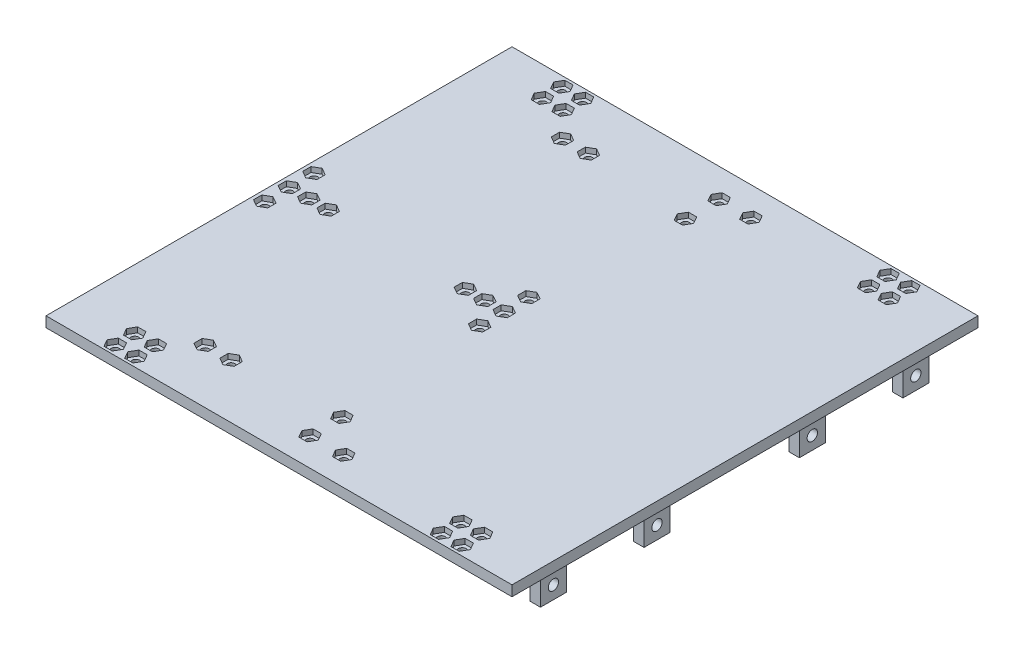
SolidWorks part; units mm, degrees
ref_plane "Alzado" through (0, 0, 0) normal (0, 0, 1) x (1, 0, 0)
ref_plane "Planta" through (0, 0, 0) normal (0, 1, 0) x (1, 0, 0)
ref_plane "Vista lateral" through (0, 0, 0) normal (1, 0, 0) x (0, 0, -1)
sketch "Croquis2" plane through (0, 0, 0) normal (0, 1, 0) x (1, 0, 0)
  line L1 (90, -90) -> (-90, -90)
  line L2 (90, -90) -> (90, 90)
  line L3 (90, 90) -> (-90, 90)
  line L4 (-90, -90) -> (-90, 90)
  line L5 (90, -90) -> (-90, 90) construction
  line L6 (90, 90) -> (-90, -90) construction
  point P0 (0, 0)
extrude "Saliente-Extruir2" add sketch "Croquis2" along normal blind 4
sketch "Croquis3" plane through (0, 0, 0) normal (0, -1, 0) x (1, 0, 0)
  line L0 (-90, 0) -> (90, 0) construction
  line L1 (-86, 75) -> (-82, 75)
  line L2 (-86, 75) -> (-86, 65)
  line L3 (-86, 65) -> (-82, 65)
  line L4 (-82, 75) -> (-82, 65)
  line L5 (-86, 75) -> (-82, 65) construction
  line L6 (-86, 65) -> (-82, 75) construction
  line L7 (-90, -90) -> (-90, 90) construction
  line L8 (90, 90) -> (90, -90) construction
  line L9 (-90, 90) -> (90, 90) construction
  line L10 (-82, 35) -> (-82, 25)
  line L11 (-86, 35) -> (-86, 25)
  line L12 (-86, 35) -> (-82, 35)
  line L13 (-86, 25) -> (-82, 25)
  line L14 (0, 90) -> (0, -90) construction
  line L16 (90, -90) -> (-90, -90) construction
  line L17 (86, 65) -> (82, 75) construction
  line L26 (86, 75) -> (82, 65) construction
  line L27 (86, 25) -> (82, 25)
  line L28 (86, 35) -> (82, 35)
  line L29 (86, 35) -> (86, 25)
  line L30 (82, 35) -> (82, 25)
  line L31 (82, 75) -> (82, 65)
  line L32 (86, 65) -> (82, 65)
  line L33 (86, 75) -> (86, 65)
  line L34 (86, 75) -> (82, 75)
  line L35 (86, -75) -> (82, -65) construction
  line L36 (86, -65) -> (82, -75) construction
  line L37 (86, -75) -> (82, -75)
  line L38 (86, -75) -> (86, -65)
  line L39 (86, -65) -> (82, -65)
  line L40 (82, -75) -> (82, -65)
  line L41 (82, -35) -> (82, -25)
  line L42 (86, -35) -> (86, -25)
  line L43 (86, -35) -> (82, -35)
  line L44 (86, -25) -> (82, -25)
  line L45 (-86, -65) -> (-82, -75) construction
  line L46 (-86, -75) -> (-82, -65) construction
  line L47 (-86, -25) -> (-82, -25)
  line L48 (-86, -35) -> (-82, -35)
  line L49 (-86, -35) -> (-86, -25)
  line L50 (-82, -35) -> (-82, -25)
  line L51 (-82, -75) -> (-82, -65)
  line L52 (-86, -65) -> (-82, -65)
  line L53 (-86, -75) -> (-86, -65)
  line L54 (-86, -75) -> (-82, -75)
  point P0 (-84, 70)
  point P29 (84, 70)
  point P38 (84, -70)
  point P47 (-84, -70)
  dimension "D1" = 4
  dimension "D2" = 15
  dimension "D3" = 10
  dimension "D4" = 4
  dimension "D6" = 30
  dimension "D5" = 2
extrude "Saliente-Extruir3" add sketch "Croquis3" along normal blind 13
sketch "Croquis4" plane through (86, 0, 0) normal (1, 0, 0) x (0, 0, -1)
  line L0 (-65, -13) -> (-75, -13) construction
  line L1 (-65, -13) -> (-65, 0) construction
  line L2 (-35, -13) -> (-35, 0) construction
  line L3 (25, -13) -> (25, 0) construction
  line L4 (65, -13) -> (65, 0) construction
  circle A0 centre (-70, -8) radius 2
  circle A1 centre (-30, -8) radius 2
  circle A2 centre (30, -8) radius 2
  circle A3 centre (70, -8) radius 2
  dimension "D1" = 4
  dimension "D4" = 5
  dimension "D2" = 5
  dimension "D3" = 5
  dimension "D5" = 5
  dimension "D6" = 5
extrude "Cortar-Extruir1" cut sketch "Croquis4" along direction (1, 0, 0) on the side against the normal up to surface (172 mm away)
sketch "Croquis5" plane through (86, 0, 0) normal (1, 0, 0) x (0, 0, -1)
  line L1 (35, -3) -> (40.7629, -3)
  line L4 (-35, -13) -> (-35, 0) construction
  line L5 (-65, 0) -> (-35, 0) construction
  line L6 (40.7629, -3) -> (35, 0)
  line L10 (65, -13) -> (65, 0) construction
  line L11 (35, 0) -> (65, 0) construction
  line L13 (59.2371, -3) -> (65, 0)
  line L19 (-65, 0) -> (-65, -3)
  line L24 (-65, -3) -> (-35, -3) construction
  line L25 (-35, 0) -> (-35, -3)
  line L30 (35, 0) -> (35, -3)
  line L31 (35, -3) -> (65, -3) construction
  line L32 (-65, 0) -> (-35, -3) construction
  line L33 (-65, -3) -> (-35, 0) construction
  line L34 (65, 0) -> (65, -3)
  line L35 (35, 0) -> (65, -3) construction
  line L36 (35, -3) -> (65, 0) construction
  line L41 (-65, -3) -> (-59.2371, -3)
  line L42 (-59.2371, -3) -> (-65, 0)
  line L43 (-35, 0) -> (-40.7629, -3)
  line L44 (-40.7629, -3) -> (-35, -3)
  line L45 (59.2371, -3) -> (65, -3)
  point P5 (-50, -1.5)
  point P14 (50, -1.5)
  dimension "D1" = 3
  dimension "D2" = 3
  dimension "D3" = 27.5
  dimension "D4" = 27.5
  dimension "D5" = 27.5
  dimension "D6" = 27.5
extrude "Saliente-Extruir7" add sketch "Croquis5" against normal blind 75 separate body
sketch "Croquis7" plane through (-86, 0, 0) normal (-1, 0, 0) x (0, 0, 1)
  line L0 (65, 0) -> (59.2371, -3) construction
  line L1 (59.2371, -3) -> (65, -3) construction
  line L2 (65, -3) -> (65, 0) construction
  line L3 (35, -3) -> (40.7629, -3) construction
  line L4 (40.7629, -3) -> (35, 0) construction
  line L5 (35, 0) -> (35, -3) construction
  line L6 (-35, 0) -> (-40.7629, -3) construction
  line L7 (-40.7629, -3) -> (-35, -3) construction
  line L8 (-35, -3) -> (-35, 0) construction
  line L9 (-65, -3) -> (-59.2371, -3) construction
  line L10 (-59.2371, -3) -> (-65, 0) construction
  line L11 (-65, 0) -> (-65, -3) construction
  line L12 (65, 0) -> (59.2371, -3)
  line L13 (59.2371, -3) -> (65, -3)
  line L14 (65, -3) -> (65, 0)
  line L15 (35, -3) -> (40.7629, -3)
  line L16 (40.7629, -3) -> (35, 0)
  line L17 (35, 0) -> (35, -3)
  line L18 (-35, 0) -> (-40.7629, -3)
  line L19 (-40.7629, -3) -> (-35, -3)
  line L20 (-35, -3) -> (-35, 0)
  line L21 (-65, -3) -> (-59.2371, -3)
  line L22 (-59.2371, -3) -> (-65, 0)
  line L23 (-65, 0) -> (-65, -3)
extrude "Saliente-Extruir8" add sketch "Croquis7" against normal blind 75 separate body
sketch "Croquis8" plane through (0, 4, 0) normal (0, 1, 0) x (1, 0, 0)
  circle A0 centre (67, -86.25) radius 1.5
  circle A1 centre (59, -86.25) radius 1.5
  circle A2 centre (59, -78.75) radius 1.5
  circle A3 centre (67, -78.75) radius 1.5
  circle A4 centre (14, -79) radius 1.5
  circle A5 centre (1, -79) radius 1.5
  circle A6 centre (1, -66.715) radius 1.5
  circle A7 centre (67, 78.75) radius 1.5
  circle A8 centre (67, 86.25) radius 1.5
  circle A9 centre (59, 86.25) radius 1.5
  circle A10 centre (59, 78.75) radius 1.5
  circle A11 centre (13.285, 79) radius 1.5
  circle A12 centre (1, 79) radius 1.5
  circle A13 centre (1, 66) radius 1.5
  circle A14 centre (-59, 78.75) radius 1.5
  circle A15 centre (-67, 78.75) radius 1.5
  circle A16 centre (-67, 86.25) radius 1.5
  circle A18 centre (-59, 86.25) radius 1.5
  circle A19 centre (-59, -78.75) radius 1.5
  circle A20 centre (-59, -86.25) radius 1.5
  circle A21 centre (-67, -78.75) radius 1.5
  circle A22 centre (-67, -86.25) radius 1.5
extrude "Cortar-Extruir2" cut sketch "Croquis8" against normal up to next (4 mm away)
sketch "Croquis9" plane through (0, 4, 0) normal (0, 1, 0) x (1, 0, 0)
  line L1 (65.4123, -89) -> (68.5877, -89)
  line L2 (68.5877, -89) -> (70.1754, -86.25)
  line L3 (70.1754, -86.25) -> (68.5877, -83.5)
  line L4 (68.5877, -83.5) -> (65.4123, -83.5)
  line L5 (65.4123, -83.5) -> (63.8246, -86.25)
  line L6 (63.8246, -86.25) -> (65.4123, -89)
  line L7 (57.4123, -89) -> (60.5877, -89)
  line L8 (60.5877, -89) -> (62.1754, -86.25)
  line L9 (62.1754, -86.25) -> (60.5877, -83.5)
  line L10 (60.5877, -83.5) -> (57.4123, -83.5)
  line L11 (57.4123, -83.5) -> (55.8246, -86.25)
  line L12 (55.8246, -86.25) -> (57.4123, -89)
  line L13 (57.4123, -81.5) -> (60.5877, -81.5)
  line L14 (60.5877, -81.5) -> (62.1754, -78.75)
  line L15 (62.1754, -78.75) -> (60.5877, -76)
  line L16 (60.5877, -76) -> (57.4123, -76)
  line L17 (57.4123, -76) -> (55.8246, -78.75)
  line L18 (55.8246, -78.75) -> (57.4123, -81.5)
  line L19 (65.4123, -81.5) -> (68.5877, -81.5)
  line L20 (68.5877, -81.5) -> (70.1754, -78.75)
  line L21 (70.1754, -78.75) -> (68.5877, -76)
  line L22 (68.5877, -76) -> (65.4123, -76)
  line L23 (65.4123, -76) -> (63.8246, -78.75)
  line L24 (63.8246, -78.75) -> (65.4123, -81.5)
  line L25 (15.5877, -81.75) -> (17.1754, -79)
  line L26 (17.1754, -79) -> (15.5877, -76.25)
  line L27 (15.5877, -76.25) -> (12.4123, -76.25)
  line L28 (12.4123, -76.25) -> (10.8246, -79)
  line L29 (10.8246, -79) -> (12.4123, -81.75)
  line L30 (12.4123, -81.75) -> (15.5877, -81.75)
  line L31 (2.5877, -81.75) -> (4.1754, -79)
  line L32 (4.1754, -79) -> (2.5877, -76.25)
  line L33 (2.5877, -76.25) -> (-0.5877, -76.25)
  line L34 (-0.5877, -76.25) -> (-2.1754, -79)
  line L35 (-2.1754, -79) -> (-0.5877, -81.75)
  line L36 (-0.5877, -81.75) -> (2.5877, -81.75)
  line L37 (2.5877, -69.465) -> (4.1754, -66.715)
  line L38 (4.1754, -66.715) -> (2.5877, -63.965)
  line L39 (2.5877, -63.965) -> (-0.5877, -63.965)
  line L40 (-0.5877, -63.965) -> (-2.1754, -66.715)
  line L41 (-2.1754, -66.715) -> (-0.5877, -69.465)
  line L42 (-0.5877, -69.465) -> (2.5877, -69.465)
  line L67 (68.5877, 76) -> (70.1754, 78.75)
  line L68 (70.1754, 78.75) -> (68.5877, 81.5)
  line L69 (68.5877, 81.5) -> (65.4123, 81.5)
  line L70 (65.4123, 81.5) -> (63.8246, 78.75)
  line L71 (63.8246, 78.75) -> (65.4123, 76)
  line L72 (65.4123, 76) -> (68.5877, 76)
  line L73 (60.5877, 76) -> (62.1754, 78.75)
  line L74 (62.1754, 78.75) -> (60.5877, 81.5)
  line L75 (60.5877, 81.5) -> (57.4123, 81.5)
  line L76 (57.4123, 81.5) -> (55.8246, 78.75)
  line L77 (55.8246, 78.75) -> (57.4123, 76)
  line L78 (57.4123, 76) -> (60.5877, 76)
  line L79 (68.5877, 83.5) -> (70.1754, 86.25)
  line L80 (70.1754, 86.25) -> (68.5877, 89)
  line L81 (68.5877, 89) -> (65.4123, 89)
  line L82 (65.4123, 89) -> (63.8246, 86.25)
  line L83 (63.8246, 86.25) -> (65.4123, 83.5)
  line L84 (65.4123, 83.5) -> (68.5877, 83.5)
  line L85 (60.5877, 83.5) -> (62.1754, 86.25)
  line L86 (62.1754, 86.25) -> (60.5877, 89)
  line L87 (60.5877, 89) -> (57.4123, 89)
  line L88 (57.4123, 89) -> (55.8246, 86.25)
  line L89 (55.8246, 86.25) -> (57.4123, 83.5)
  line L90 (57.4123, 83.5) -> (60.5877, 83.5)
  line L91 (14.8727, 76.25) -> (16.4604, 79)
  line L92 (16.4604, 79) -> (14.8727, 81.75)
  line L93 (14.8727, 81.75) -> (11.6972, 81.75)
  line L94 (11.6972, 81.75) -> (10.1095, 79)
  line L95 (10.1095, 79) -> (11.6972, 76.25)
  line L96 (11.6972, 76.25) -> (14.8727, 76.25)
  line L97 (2.5877, 76.25) -> (4.1754, 79)
  line L98 (4.1754, 79) -> (2.5877, 81.75)
  line L99 (2.5877, 81.75) -> (-0.5877, 81.75)
  line L100 (-0.5877, 81.75) -> (-2.1754, 79)
  line L101 (-2.1754, 79) -> (-0.5877, 76.25)
  line L102 (-0.5877, 76.25) -> (2.5877, 76.25)
  line L103 (2.5877, 63.25) -> (4.1754, 66)
  line L104 (4.1754, 66) -> (2.5877, 68.75)
  line L105 (2.5877, 68.75) -> (-0.5877, 68.75)
  line L106 (-0.5877, 68.75) -> (-2.1754, 66)
  line L107 (-2.1754, 66) -> (-0.5877, 63.25)
  line L108 (-0.5877, 63.25) -> (2.5877, 63.25)
  line L109 (-65.4123, 83.5) -> (-63.8246, 86.25)
  line L110 (-63.8246, 86.25) -> (-65.4123, 89)
  line L111 (-65.4123, 89) -> (-68.5877, 89)
  line L112 (-68.5877, 89) -> (-70.1754, 86.25)
  line L113 (-70.1754, 86.25) -> (-68.5877, 83.5)
  line L114 (-68.5877, 83.5) -> (-65.4123, 83.5)
  line L115 (-57.4123, 83.5) -> (-55.8246, 86.25)
  line L116 (-55.8246, 86.25) -> (-57.4123, 89)
  line L117 (-57.4123, 89) -> (-60.5877, 89)
  line L118 (-60.5877, 89) -> (-62.1754, 86.25)
  line L119 (-62.1754, 86.25) -> (-60.5877, 83.5)
  line L120 (-60.5877, 83.5) -> (-57.4123, 83.5)
  line L121 (-57.4123, 76) -> (-55.8246, 78.75)
  line L122 (-55.8246, 78.75) -> (-57.4123, 81.5)
  line L123 (-57.4123, 81.5) -> (-60.5877, 81.5)
  line L124 (-60.5877, 81.5) -> (-62.1754, 78.75)
  line L125 (-62.1754, 78.75) -> (-60.5877, 76)
  line L126 (-60.5877, 76) -> (-57.4123, 76)
  line L127 (-65.4123, 76) -> (-63.8246, 78.75)
  line L128 (-63.8246, 78.75) -> (-65.4123, 81.5)
  line L129 (-65.4123, 81.5) -> (-68.5877, 81.5)
  line L130 (-68.5877, 81.5) -> (-70.1754, 78.75)
  line L131 (-70.1754, 78.75) -> (-68.5877, 76)
  line L132 (-68.5877, 76) -> (-65.4123, 76)
  line L133 (-57.4123, -89) -> (-55.8246, -86.25)
  line L134 (-55.8246, -86.25) -> (-57.4123, -83.5)
  line L135 (-57.4123, -83.5) -> (-60.5877, -83.5)
  line L136 (-60.5877, -83.5) -> (-62.1754, -86.25)
  line L137 (-62.1754, -86.25) -> (-60.5877, -89)
  line L138 (-60.5877, -89) -> (-57.4123, -89)
  line L139 (-65.4123, -89) -> (-63.8246, -86.25)
  line L140 (-63.8246, -86.25) -> (-65.4123, -83.5)
  line L141 (-65.4123, -83.5) -> (-68.5877, -83.5)
  line L142 (-68.5877, -83.5) -> (-70.1754, -86.25)
  line L143 (-70.1754, -86.25) -> (-68.5877, -89)
  line L144 (-68.5877, -89) -> (-65.4123, -89)
  line L145 (-57.4123, -81.5) -> (-55.8246, -78.75)
  line L146 (-55.8246, -78.75) -> (-57.4123, -76)
  line L147 (-57.4123, -76) -> (-60.5877, -76)
  line L148 (-60.5877, -76) -> (-62.1754, -78.75)
  line L149 (-62.1754, -78.75) -> (-60.5877, -81.5)
  line L150 (-60.5877, -81.5) -> (-57.4123, -81.5)
  line L151 (-65.4123, -81.5) -> (-63.8246, -78.75)
  line L152 (-63.8246, -78.75) -> (-65.4123, -76)
  line L153 (-65.4123, -76) -> (-68.5877, -76)
  line L154 (-68.5877, -76) -> (-70.1754, -78.75)
  line L155 (-70.1754, -78.75) -> (-68.5877, -81.5)
  line L156 (-68.5877, -81.5) -> (-65.4123, -81.5)
  circle A0 centre (67, -86.25) radius 2.75 construction
  circle A1 centre (59, -86.25) radius 2.75 construction
  circle A2 centre (59, -78.75) radius 2.75 construction
  circle A3 centre (67, -78.75) radius 2.75 construction
  circle A4 centre (14, -79) radius 2.75 construction
  circle A5 centre (1, -79) radius 2.75 construction
  circle A6 centre (1, -66.715) radius 2.75 construction
  circle A7 centre (-59, -86.25) radius 2.75 construction
  circle A8 centre (-67, -86.25) radius 2.75 construction
  circle A9 centre (-59, -78.75) radius 2.75 construction
  circle A10 centre (-67, -78.75) radius 2.75 construction
  circle A11 centre (67, 78.75) radius 2.75 construction
  circle A12 centre (59, 78.75) radius 2.75 construction
  circle A13 centre (67, 86.25) radius 2.75 construction
  circle A14 centre (59, 86.25) radius 2.75 construction
  circle A15 centre (13.285, 79) radius 2.75 construction
  circle A16 centre (1, 79) radius 2.75 construction
  circle A17 centre (1, 66) radius 2.75 construction
  circle A18 centre (-67, 86.25) radius 2.75 construction
  circle A19 centre (-59, 86.25) radius 2.75 construction
  circle A20 centre (-59, 78.75) radius 2.75 construction
  circle A21 centre (-67, 78.75) radius 2.75 construction
  dimension "D1" = 5.5
  dimension "D2" = 5.5
  dimension "D3" = 5.5
  dimension "D4" = 5.5
  dimension "D5" = 5.5
  dimension "D6" = 5.5
  dimension "D7" = 5.5
  dimension "D8" = 5.5
  dimension "D9" = 5.5
  dimension "D10" = 5.5
  dimension "D11" = 5.5
  dimension "D12" = 5.5
  dimension "D13" = 5.5
  dimension "D14" = 5.5
  dimension "D15" = 5.5
  dimension "D16" = 5.5
  dimension "D17" = 5.5
  dimension "D18" = 5.5
  dimension "D19" = 5.5
  dimension "D20" = 5.5
  dimension "D21" = 5.5
  dimension "D22" = 5.5
extrude "Cortar-Extruir3" cut sketch "Croquis9" against normal blind 2
sketch "Croquis10" plane through (0, 4, 0) normal (0, 1, 0) x (1, 0, 0)
  circle A0 centre (-49.5, -69) radius 1.5
  circle A2 centre (-78.5, 0) radius 1.5 construction
  circle A3 centre (-86, 9.5) radius 1.5 construction
  circle A4 centre (-86, -9.5) radius 1.5 construction
  circle A5 centre (-86, 0) radius 1.5 construction
  circle A7 centre (-78.5, 0) radius 1.5
  circle A8 centre (-86, 9.5) radius 1.5
  circle A9 centre (-86, -9.5) radius 1.5
  circle A10 centre (-86, 0) radius 1.5
  circle A11 centre (-39.5, -69) radius 1.5
  circle A12 centre (-10.5, 0) radius 1.5 construction
  circle A13 centre (-3, 9.5) radius 1.5 construction
  circle A14 centre (-3, 0) radius 1.5 construction
  circle A15 centre (-3, -9.5) radius 1.5 construction
  circle A16 centre (-39.5, 69) radius 1.5 construction
  circle A17 centre (-49.5, 69) radius 1.5 construction
  circle A18 centre (-71, 0) radius 1.5 construction
  circle A19 centre (-10.5, 0) radius 1.5
  circle A20 centre (-3, 9.5) radius 1.5
  circle A21 centre (-3, 0) radius 1.5
  circle A22 centre (-3, -9.5) radius 1.5
  circle A23 centre (-39.5, 69) radius 1.5
  circle A24 centre (-49.5, 69) radius 1.5
  circle A25 centre (-71, 0) radius 1.5
  circle A26 centre (-18, 0) radius 1.5 construction
  circle A27 centre (-18, 0) radius 1.5
  dimension "D1" = 3
  dimension "D2" = 20.6754
  dimension "D3" = 30.6754
  dimension "D4" = 12.75
extrude "Cortar-Extruir4" cut sketch "Croquis10" against normal up to next (4 mm away)
sketch "Croquis11" plane through (0, 4, 0) normal (0, 1, 0) x (1, 0, 0)
  line L1 (-88.75, -11.0877) -> (-86, -12.6754)
  line L2 (-86, -12.6754) -> (-83.25, -11.0877)
  line L3 (-83.25, -11.0877) -> (-83.25, -7.9123)
  line L4 (-83.25, -7.9123) -> (-86, -6.3246)
  line L5 (-86, -6.3246) -> (-88.75, -7.9123)
  line L6 (-88.75, -7.9123) -> (-88.75, -11.0877)
  line L7 (-88.75, -1.5877) -> (-86, -3.1754)
  line L8 (-86, -3.1754) -> (-83.25, -1.5877)
  line L9 (-83.25, -1.5877) -> (-83.25, 1.5877)
  line L10 (-83.25, 1.5877) -> (-86, 3.1754)
  line L11 (-86, 3.1754) -> (-88.75, 1.5877)
  line L12 (-88.75, 1.5877) -> (-88.75, -1.5877)
  line L13 (-88.75, 7.9123) -> (-86, 6.3246)
  line L14 (-86, 6.3246) -> (-83.25, 7.9123)
  line L15 (-83.25, 7.9123) -> (-83.25, 11.0877)
  line L16 (-83.25, 11.0877) -> (-86, 12.6754)
  line L17 (-86, 12.6754) -> (-88.75, 11.0877)
  line L18 (-88.75, 11.0877) -> (-88.75, 7.9123)
  line L19 (-81.25, -1.5877) -> (-78.5, -3.1754)
  line L20 (-78.5, -3.1754) -> (-75.75, -1.5877)
  line L21 (-75.75, -1.5877) -> (-75.75, 1.5877)
  line L22 (-75.75, 1.5877) -> (-78.5, 3.1754)
  line L23 (-78.5, 3.1754) -> (-81.25, 1.5877)
  line L24 (-81.25, 1.5877) -> (-81.25, -1.5877)
  line L25 (-73.75, -1.5877) -> (-71, -3.1754)
  line L26 (-71, -3.1754) -> (-68.25, -1.5877)
  line L27 (-68.25, -1.5877) -> (-68.25, 1.5877)
  line L28 (-68.25, 1.5877) -> (-71, 3.1754)
  line L29 (-71, 3.1754) -> (-73.75, 1.5877)
  line L30 (-73.75, 1.5877) -> (-73.75, -1.5877)
  line L31 (-52.25, 67.4123) -> (-49.5, 65.8246)
  line L32 (-49.5, 65.8246) -> (-46.75, 67.4123)
  line L33 (-46.75, 67.4123) -> (-46.75, 70.5877)
  line L34 (-46.75, 70.5877) -> (-49.5, 72.1754)
  line L35 (-49.5, 72.1754) -> (-52.25, 70.5877)
  line L36 (-52.25, 70.5877) -> (-52.25, 67.4123)
  line L37 (-42.25, 67.4123) -> (-39.5, 65.8246)
  line L38 (-39.5, 65.8246) -> (-36.75, 67.4123)
  line L39 (-36.75, 67.4123) -> (-36.75, 70.5877)
  line L40 (-36.75, 70.5877) -> (-39.5, 72.1754)
  line L41 (-39.5, 72.1754) -> (-42.25, 70.5877)
  line L42 (-42.25, 70.5877) -> (-42.25, 67.4123)
  line L43 (-5.75, -11.0877) -> (-3, -12.6754)
  line L44 (-3, -12.6754) -> (-0.25, -11.0877)
  line L45 (-0.25, -11.0877) -> (-0.25, -7.9123)
  line L46 (-0.25, -7.9123) -> (-3, -6.3246)
  line L47 (-3, -6.3246) -> (-5.75, -7.9123)
  line L48 (-5.75, -7.9123) -> (-5.75, -11.0877)
  line L49 (-5.75, -1.5877) -> (-3, -3.1754)
  line L50 (-3, -3.1754) -> (-0.25, -1.5877)
  line L51 (-0.25, -1.5877) -> (-0.25, 1.5877)
  line L52 (-0.25, 1.5877) -> (-3, 3.1754)
  line L53 (-3, 3.1754) -> (-5.75, 1.5877)
  line L54 (-5.75, 1.5877) -> (-5.75, -1.5877)
  line L55 (-5.75, 7.9123) -> (-3, 6.3246)
  line L56 (-3, 6.3246) -> (-0.25, 7.9123)
  line L57 (-0.25, 7.9123) -> (-0.25, 11.0877)
  line L58 (-0.25, 11.0877) -> (-3, 12.6754)
  line L59 (-3, 12.6754) -> (-5.75, 11.0877)
  line L60 (-5.75, 11.0877) -> (-5.75, 7.9123)
  line L61 (-13.25, -1.5877) -> (-10.5, -3.1754)
  line L62 (-10.5, -3.1754) -> (-7.75, -1.5877)
  line L63 (-7.75, -1.5877) -> (-7.75, 1.5877)
  line L64 (-7.75, 1.5877) -> (-10.5, 3.1754)
  line L65 (-10.5, 3.1754) -> (-13.25, 1.5877)
  line L66 (-13.25, 1.5877) -> (-13.25, -1.5877)
  line L67 (-20.75, -1.5877) -> (-18, -3.1754)
  line L68 (-18, -3.1754) -> (-15.25, -1.5877)
  line L69 (-15.25, -1.5877) -> (-15.25, 1.5877)
  line L70 (-15.25, 1.5877) -> (-18, 3.1754)
  line L71 (-18, 3.1754) -> (-20.75, 1.5877)
  line L72 (-20.75, 1.5877) -> (-20.75, -1.5877)
  line L73 (-52.25, -70.5877) -> (-49.5, -72.1754)
  line L74 (-49.5, -72.1754) -> (-46.75, -70.5877)
  line L75 (-46.75, -70.5877) -> (-46.75, -67.4123)
  line L76 (-46.75, -67.4123) -> (-49.5, -65.8246)
  line L77 (-49.5, -65.8246) -> (-52.25, -67.4123)
  line L78 (-52.25, -67.4123) -> (-52.25, -70.5877)
  line L79 (-42.25, -70.5877) -> (-39.5, -72.1754)
  line L80 (-39.5, -72.1754) -> (-36.75, -70.5877)
  line L81 (-36.75, -70.5877) -> (-36.75, -67.4123)
  line L82 (-36.75, -67.4123) -> (-39.5, -65.8246)
  line L83 (-39.5, -65.8246) -> (-42.25, -67.4123)
  line L84 (-42.25, -67.4123) -> (-42.25, -70.5877)
  circle A0 centre (-86, -9.5) radius 2.75 construction
  circle A1 centre (-86, 0) radius 2.75 construction
  circle A2 centre (-86, 9.5) radius 2.75 construction
  circle A3 centre (-78.5, 0) radius 2.75 construction
  circle A4 centre (-71, 0) radius 2.75 construction
  circle A5 centre (-49.5, 69) radius 2.75 construction
  circle A6 centre (-39.5, 69) radius 2.75 construction
  circle A7 centre (-3, -9.5) radius 2.75 construction
  circle A8 centre (-3, 0) radius 2.75 construction
  circle A9 centre (-3, 9.5) radius 2.75 construction
  circle A10 centre (-10.5, 0) radius 2.75 construction
  circle A11 centre (-18, 0) radius 2.75 construction
  circle A12 centre (-49.5, -69) radius 2.75 construction
  circle A13 centre (-39.5, -69) radius 2.75 construction
  dimension "D1" = 5.5
  dimension "D2" = 5.5
  dimension "D3" = 5.5
  dimension "D4" = 5.5
extrude "Cortar-Extruir5" cut sketch "Croquis11" against normal blind 2
sketch "Croquis12" plane through (11, 0, 0) normal (-1, 0, 0) x (0, 0, 1)
  line L0 (-65, -3) -> (-59.2371, -3) construction
  line L1 (-59.2371, -3) -> (-65, 0) construction
  line L2 (-65, 0) -> (-65, -3) construction
  line L3 (35, -3) -> (40.7629, -3)
  line L4 (40.7629, -3) -> (35, 0)
  line L5 (35, 0) -> (35, -3)
  line L7 (40.7629, -3) -> (35, 0) construction
  line L8 (35, 0) -> (35, -3)
  line L9 (-35, 0) -> (-40.7629, -3) construction
  line L10 (-40.7629, -3) -> (-35, -3) construction
  line L11 (-35, -3) -> (-35, 0) construction
  line L12 (65, 0) -> (59.2371, -3) construction
  line L13 (59.2371, -3) -> (65, -3) construction
  line L14 (65, -3) -> (65, 0) construction
  line L15 (-65, -3) -> (-59.2371, -3) construction
  line L16 (-59.2371, -3) -> (-65, 0) construction
  line L17 (-65, 0) -> (-65, -3) construction
  line L18 (-35, 0) -> (-40.7629, -3) construction
  line L19 (-40.7629, -3) -> (-35, -3) construction
  line L20 (-35, -3) -> (-35, 0) construction
  line L21 (65, 0) -> (59.2371, -3) construction
  line L22 (59.2371, -3) -> (65, -3) construction
  line L23 (65, -3) -> (65, 0)
  line L25 (35, -1.5) -> (40.7629, -1.5) construction
  line L26 (40.7629, -3) -> (35, -3) construction
  line L27 (40.7629, 0) -> (35, -3) construction
  line L28 (40.7629, 0) -> (29.2371, 0) construction
  line L29 (29.2371, 0) -> (35, -3)
  line L30 (35, 0) -> (29.2371, 0)
  line L31 (65, -1.5) -> (59.2371, -1.5) construction
  line L32 (65, -3) -> (59.2371, 0) construction
  line L33 (59.2371, 0) -> (65, 0) construction
  line L34 (70.7629, 0) -> (65, 0)
  line L35 (65, -3) -> (70.7629, 0)
  line L36 (-35, -1.5) -> (-40.7629, -1.5) construction
  line L37 (-65, -1.5) -> (-59.2371, -1.5) construction
  line L38 (-59.2371, 0) -> (-65, -3) construction
  line L39 (-65, 0) -> (-59.2371, 0) construction
  line L40 (-65, 0) -> (-70.7629, 0) construction
  line L41 (-70.7629, 0) -> (-65, -3) construction
  line L42 (-65, -3) -> (-70.7629, 0)
  line L43 (-70.7629, 0) -> (-65, 0)
  line L44 (-65, 0) -> (-65, -3)
  line L45 (-35, -3) -> (-40.7629, 0) construction
  line L46 (-40.7629, 0) -> (-35, 0) construction
  line L47 (-29.2371, 0) -> (-35, 0) construction
  line L48 (-35, -3) -> (-29.2371, 0) construction
  line L49 (-35, -3) -> (-29.2371, 0)
  line L50 (-29.2371, 0) -> (-35, 0)
  line L51 (-35, 0) -> (-35, -3)
  line M35 (35, 0) -> (35, -3)
  dimension "D1" = 0
extrude "Saliente-Extruir9" add sketch "Croquis12" against normal up to surface (71 mm away) contours L30 L29 M35 | L23 L35 L34 | L50 L51 L49 | L44 L43 L42 up to face at (82, -8, -72)
sketch "Croquis13" plane through (-11, 0, 0) normal (1, 0, 0) x (0, 0, -1)
  line L0 (-65, 0) -> (-65, -3) construction
  line L1 (-65, -3) -> (-59.2371, -3) construction
  line L2 (-59.2371, -3) -> (-65, 0) construction
  line L3 (-35, -3) -> (-35, 0) construction
  line L4 (-35, 0) -> (-40.7629, -3) construction
  line L5 (-40.7629, -3) -> (-35, -3) construction
  line L6 (35, 0) -> (35, -3) construction
  line L7 (35, -3) -> (40.7629, -3) construction
  line L8 (40.7629, -3) -> (35, 0) construction
  line L9 (65, -3) -> (65, 0) construction
  line L10 (65, 0) -> (59.2371, -3) construction
  line L11 (59.2371, -3) -> (65, -3) construction
  line L12 (-65, 0) -> (-65, -3)
  line L13 (-65, -3) -> (-59.2371, -3) construction
  line L14 (-59.2371, -3) -> (-65, 0) construction
  line L15 (-35, -3) -> (-35, 0)
  line L16 (-35, 0) -> (-40.7629, -3) construction
  line L17 (-40.7629, -3) -> (-35, -3) construction
  line L18 (35, 0) -> (35, -3)
  line L19 (35, -3) -> (40.7629, -3) construction
  line L20 (40.7629, -3) -> (35, 0) construction
  line L21 (65, -3) -> (65, 0)
  line L22 (65, 0) -> (59.2371, -3) construction
  line L23 (59.2371, -3) -> (65, -3) construction
  line L24 (65, -1.5) -> (59.2371, -1.5) construction
  line L25 (35, -1.5) -> (40.7629, -1.5) construction
  line L26 (-35, -1.5) -> (-40.7629, -1.5) construction
  line L27 (-65, -1.5) -> (-59.2371, -1.5) construction
  line L28 (65, -3) -> (59.2371, 0) construction
  line L29 (59.2371, 0) -> (70.7629, 0) construction
  line L30 (65, -3) -> (70.7629, 0)
  line L31 (40.7629, 0) -> (35, -3) construction
  line L32 (35, 0) -> (40.7629, 0) construction
  line L33 (35, 0) -> (29.2371, 0)
  line L34 (29.2371, 0) -> (35, -3)
  line L35 (-35, -3) -> (-40.7629, 0) construction
  line L36 (-40.7629, 0) -> (-35, 0) construction
  line L37 (-29.2371, 0) -> (-35, 0)
  line L38 (-35, -3) -> (-29.2371, 0)
  line L39 (-59.2371, 0) -> (-65, -3) construction
  line L40 (-65, 0) -> (-59.2371, 0) construction
  line L41 (-65, 0) -> (-70.7629, 0)
  line L42 (-70.7629, 0) -> (-65, -3)
  line L44 (65, 0) -> (70.7629, 0)
  point P30 (65, 0)
extrude "Saliente-Extruir11" add sketch "Croquis13" against normal up to next
sketch "Croquis14" plane through (0, 0, 0) normal (0, -1, 0) x (1, 0, 0)
  circle A0 centre (-49.5, -69) radius 1.5 construction
  circle A1 centre (-39.5, 69) radius 1.5 construction
  circle A2 centre (-49.5, 69) radius 1.5 construction
  circle A3 centre (-49.5, -69) radius 1.5
  circle A4 centre (-39.5, 69) radius 1.5
  circle A5 centre (-49.5, 69) radius 1.5
  circle A6 centre (-39.5, -69) radius 1.5 construction
  circle A7 centre (-39.5, -69) radius 1.5
extrude "Cortar-Extruir8" cut sketch "Croquis14" along normal up to next
sketch "Croquis16" plane through (86, 0, 0) normal (1, 0, 0) x (0, 0, -1)
  line L0 (59.2371, -3) -> (60.236, -3)
  line L1 (59.2371, -3) -> (65, -3) construction
  line L2 (60.236, -3) -> (60.236, -2.48)
  line L3 (65, 0) -> (59.2371, -3) construction
  line L4 (60.236, -2.48) -> (59.2371, -3)
  dimension "D1" = 0.52
extrude "Cortar-Extruir9" cut sketch "Croquis16" against normal through all
sketch "Croquis17" plane through (86, 0, 0) normal (1, 0, 0) x (0, 0, -1)
  line L0 (40.7629, -3) -> (39.7629, -3)
  line L1 (35, -3) -> (40.7629, -3) construction
  line L2 (39.7629, -3) -> (39.7629, -2.4794)
  line L3 (40.7629, -3) -> (35, 0) construction
  line L4 (39.7629, -2.4794) -> (40.7629, -3)
  dimension "D1" = 0.5206
extrude "Cortar-Extruir10" cut sketch "Croquis17" against normal through all
sketch "Croquis18" plane through (86, 0, 0) normal (1, 0, 0) x (0, 0, -1)
  line L0 (-40.7629, -3) -> (-39.7629, -3)
  line L1 (-40.7629, -3) -> (-35, -3) construction
  line L2 (-39.7629, -3) -> (-39.7629, -2.4794)
  line L3 (-35, 0) -> (-40.7629, -3) construction
  line L4 (-39.7629, -2.4794) -> (-40.7629, -3)
  dimension "D1" = 0.5206
extrude "Cortar-Extruir11" cut sketch "Croquis18" against normal through all
sketch "Croquis19" plane through (86, 0, 0) normal (1, 0, 0) x (0, 0, -1)
  line L0 (-59.2371, -3) -> (-60.2371, -3)
  line L1 (-65, -3) -> (-59.2371, -3) construction
  line L2 (-60.2371, -3) -> (-60.2371, -2.4794)
  line L3 (-59.2371, -3) -> (-65, 0) construction
  line L4 (-60.2371, -2.4794) -> (-59.2371, -3)
  dimension "D1" = 0.5206
extrude "Cortar-Extruir12" cut sketch "Croquis19" against normal through all
sketch "Croquis22" plane through (86, 0, 0) normal (1, 0, 0) x (0, 0, -1)
  line L0 (38, 0) -> (35, 0)
  line L1 (65, 0) -> (62, 0)
  line L2 (65, 0) -> (65, 1)
  line L3 (65, 1) -> (62, 1)
  line L4 (62, 0) -> (62, 1)
  line L5 (65, 0) -> (62, 1) construction
  line L6 (65, 1) -> (62, 0) construction
  line L7 (35, 0) -> (35, 1)
  line L8 (38, 1) -> (35, 1)
  line L9 (38, 0) -> (38, 1)
  point P4 (63.5, 0.5)
  dimension "D1" = 3
  dimension "D2" = 1
  dimension "D3" = 2
extrude "Cortar-Extruir13" cut sketch "Croquis22" against normal up to surface (75 mm away) up to face at (11, -1.696, -64.247)
sketch "Croquis23" plane through (86, 0, 0) normal (1, 0, 0) x (0, 0, -1)
  line L0 (-62, 0) -> (-65, 0)
  line L1 (-35, 0) -> (-38, 0)
  line L2 (-35, 0) -> (-35, 1)
  line L3 (-35, 1) -> (-38, 1)
  line L4 (-38, 0) -> (-38, 1)
  line L5 (-35, 0) -> (-38, 1) construction
  line L6 (-35, 1) -> (-38, 0) construction
  line L7 (-65, 0) -> (-65, 1)
  line L8 (-62, 1) -> (-65, 1)
  line L9 (-62, 0) -> (-62, 1)
  point P4 (-36.5, 0.5)
  dimension "D1" = 1
  dimension "D2" = 3
  dimension "D3" = 2
extrude "Cortar-Extruir14" cut sketch "Croquis23" against normal up to surface (75 mm away) up to face at (11, -1.6959, 35.7526)
sketch "Croquis24" plane through (-86, 0, 0) normal (-1, 0, 0) x (0, 0, 1)
  line L0 (38, 0) -> (35, 0)
  line L1 (65, 0) -> (62, 0)
  line L2 (65, 0) -> (65, 1)
  line L3 (65, 1) -> (62, 1)
  line L4 (62, 0) -> (62, 1)
  line L5 (65, 0) -> (62, 1) construction
  line L6 (65, 1) -> (62, 0) construction
  line L7 (35, 0) -> (35, 1)
  line L8 (38, 1) -> (35, 1)
  line L9 (38, 0) -> (38, 1)
  point P4 (63.5, 0.5)
  dimension "D1" = 1
  dimension "D2" = 3
  dimension "D3" = 2
extrude "Cortar-Extruir15" cut sketch "Croquis24" against normal up to surface (75 mm away)
sketch "Croquis25" plane through (-86, 0, 0) normal (-1, 0, 0) x (0, 0, 1)
  line L0 (-62, 0) -> (-65, 0)
  line L1 (-35, 0) -> (-38, 0)
  line L2 (-35, 0) -> (-35, 1)
  line L3 (-35, 1) -> (-38, 1)
  line L4 (-38, 0) -> (-38, 1)
  line L5 (-35, 0) -> (-38, 1) construction
  line L6 (-35, 1) -> (-38, 0) construction
  line L7 (-65, 0) -> (-65, 1)
  line L8 (-62, 1) -> (-65, 1)
  line L9 (-62, 0) -> (-62, 1)
  point P4 (-36.5, 0.5)
  dimension "D1" = 1
  dimension "D2" = 3
  dimension "D3" = 2
extrude "Cortar-Extruir16" cut sketch "Croquis25" against normal up to surface (75 mm away)
sketch "Croquis26" plane through (0, 0, 0) normal (0, -1, 0) x (1, 0, 0)
  line L0 (86, -62) -> (86, -38) construction
  line L1 (11, -38) -> (11, -62) construction
  line L2 (11, -50) -> (86, -50) construction
  line L3 (11, -62) -> (86, -62) construction
  line L4 (86, -57) -> (11, -57)
  line L5 (86, -57) -> (86, -53)
  line L6 (86, -53) -> (11, -53)
  line L7 (11, -57) -> (11, -53)
  line L8 (86, -57) -> (11, -53) construction
  line L9 (86, -53) -> (11, -57) construction
  line L10 (11, -47) -> (86, -47)
  line L11 (11, -47) -> (11, -43)
  line L12 (11, -43) -> (86, -43)
  line L13 (86, -47) -> (86, -43)
  line L14 (11, -47) -> (86, -43) construction
  line L15 (11, -43) -> (86, -47) construction
  line L16 (11, -38) -> (86, -38) construction
  line L17 (86, 47) -> (11, 47)
  line L18 (86, 43) -> (86, 47)
  line L19 (86, 43) -> (11, 43)
  line L20 (11, 57) -> (86, 57)
  line L21 (86, 53) -> (86, 57)
  line L22 (11, 53) -> (86, 53)
  line L23 (11, 53) -> (11, 57)
  line L24 (11, 43) -> (11, 47)
  line L25 (-11, -53) -> (-86, -53)
  line L26 (-11, -57) -> (-11, -53)
  line L27 (-11, -57) -> (-86, -57)
  line L28 (-86, -43) -> (-11, -43)
  line L29 (-11, -47) -> (-11, -43)
  line L30 (-86, -47) -> (-11, -47)
  line L31 (-86, -47) -> (-86, -43)
  line L32 (-86, -57) -> (-86, -53)
  line L33 (-11, 47) -> (-86, 47)
  line L34 (-11, 43) -> (-11, 47)
  line L35 (-11, 43) -> (-86, 43)
  line L36 (-86, 57) -> (-11, 57)
  line L37 (-11, 53) -> (-11, 57)
  line L38 (-86, 53) -> (-11, 53)
  line L39 (-86, 53) -> (-86, 57)
  line L40 (-86, 43) -> (-86, 47)
  point P14 (48.5, -55)
  point P19 (48.5, -45)
  dimension "D1" = 5
  dimension "D2" = 3
  dimension "D3" = 3
  dimension "D4" = 5
  dimension "D5" = 2
  dimension "D6" = 2
extrude "Cortar-Extruir17" cut sketch "Croquis26" against normal blind 1
